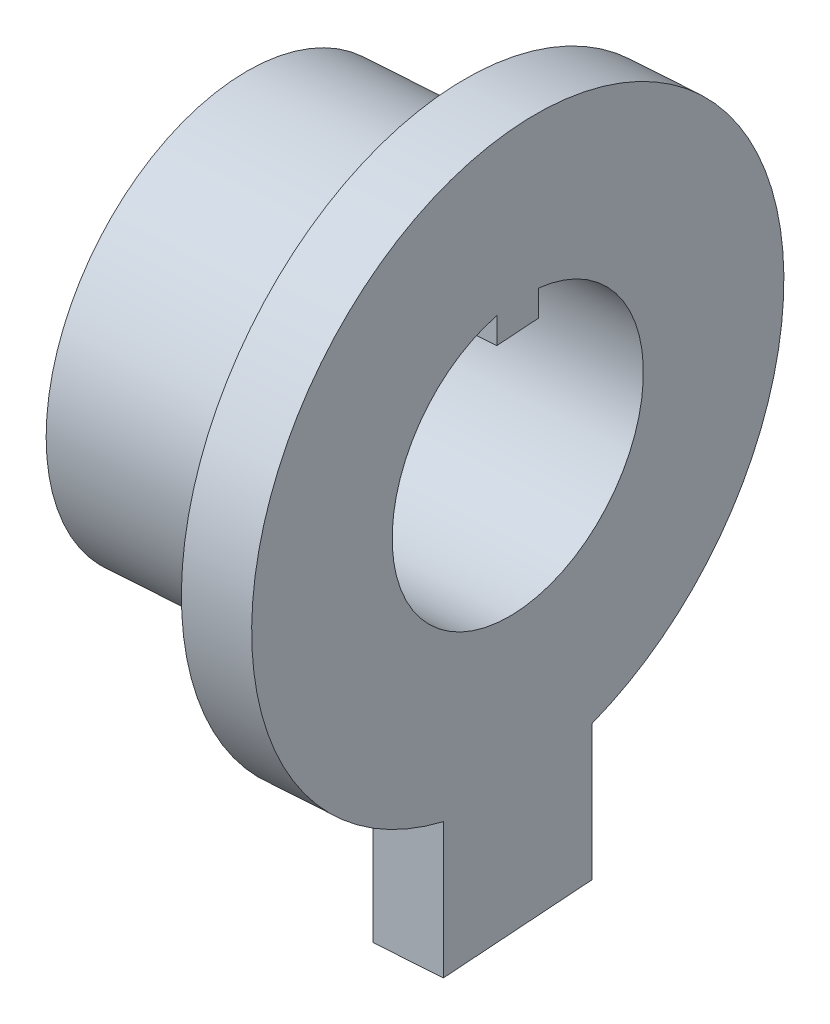
SolidWorks part; units mm, degrees
ref_plane "Plan de face" through (0, 0, 0) normal (0, 0, 1) x (1, 0, 0)
ref_plane "Plan de dessus" through (0, 0, 0) normal (0, 1, 0) x (1, 0, 0)
ref_plane "Plan de droite" through (0, 0, 0) normal (1, 0, 0) x (0, 0, -1)
ref_plane "Plan1" through (0, 72.3954, 0) normal (0, 1, 0) x (-1, 0, 0)
sketch "Esquisse1" plane through (0, 72.3954, 0) normal (0, 1, 0) x (-1, 0, 0)
  line L0 (91.3976, 206.0176) -> (92.3577, 191.7499)
  line L1 (92.3577, 191.7499) -> (95.6503, 191.9714)
  line L2 (95.6503, 191.9714) -> (94.6902, 206.2392)
  line L3 (94.6902, 206.2392) -> (91.3976, 206.0176)
  line L4 (92.6705, 191.7709) -> (95.6368, 191.9705) construction
  dimension "D1" = 14.3
  dimension "D2" = 3.3
revolve "Révolution1" add sketch "Esquisse1" angle 360 about L4
sketch "Esquisse2" plane through (-108.0789, 0, 7.2728) normal (-0.9977, 0, 0.0671) x (0.0671, 0, 0.9977)
  circle A0 centre (185.1163, 72.3954) radius 10.125
  dimension "D1" = 20.25
extrude "Boss.-Extru.1" add sketch "Esquisse2" along normal blind 10
sketch "Esquisse3" plane through (-104.7864, 0, 7.0512) normal (0.9977, 0, -0.0671) x (-0.0671, 0, -0.9977)
  line L0 (-186.2413, 77.751) -> (-186.2413, 79.051)
  line L1 (-183.9913, 79.051) -> (-183.9913, 77.751)
  line L2 (-183.9913, 77.751) -> (-186.2413, 77.751)
  line L3 (55, 72.3954) -> (-55, 72.3954) construction
  arc A0 (-186.2413, 79.051) -> (-183.9913, 79.051) centre (-185.1163, 72.3954) ccw
  dimension "D1" = 6.75
  dimension "D4" = 1.3
  dimension "D2" = 2.25
  dimension "D3" = 1.125
extrude "Enlèv. mat.-Extru.1" cut sketch "Esquisse3" against normal through all
ref_plane "Plan5" through (0, 65.6926, 0) normal (0, 1, 0) x (-1, 0, 0)
sketch "Esquisse8" plane through (-108.0789, 0, 7.2728) normal (-0.9977, 0, 0.0671) x (0.0671, 0, 0.9977)
  line L0 (181.1163, 58.6663) -> (181.1163, 51.8954)
  line L1 (181.1163, 51.8954) -> (189.1163, 51.8954)
  line L2 (189.1163, 51.8954) -> (189.1163, 58.6663)
  circle A0 centre (185.1163, 72.3954) radius 14.3 construction
  arc A1 (181.1163, 58.6663) -> (189.1163, 58.6663) centre (185.1163, 72.3954) ccw
  dimension "D1" = 8
  dimension "D2" = 4
  dimension "D3" = 20.5
extrude "Boss.-Extru.2" add sketch "Esquisse8" against normal up to surface (3.3 mm away) up to face at (-92.3577, 75.0496, 191.7499)
